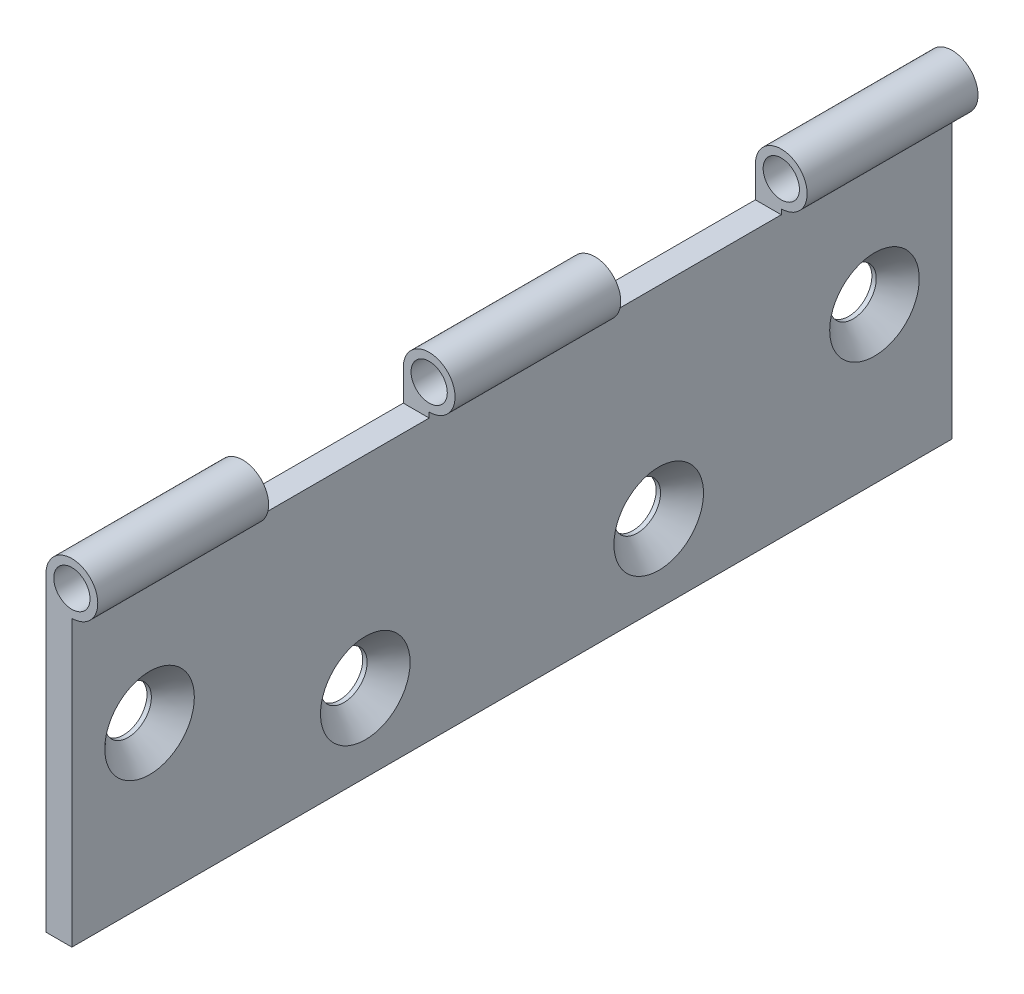
SolidWorks part; units mm, degrees
ref_plane "Front" through (0, 0, 0) normal (0, 0, 1) x (1, 0, 0)
ref_plane "Top" through (0, 0, 0) normal (0, 1, 0) x (1, 0, 0)
ref_plane "Right" through (0, 0, 0) normal (1, 0, 0) x (0, 0, -1)
sketch "Sketch1" plane through (0, 0, 0) normal (0, 0, 1) x (1, 0, 0)
  line L0 (0, 0) -> (0, 60)
  dimension "D1" = 60
extrude "Extrude-Thin1" add sketch "Sketch1" along normal mid plane 170 thin
sketch "Sketch3" plane through (0, 0, 85) normal (0, 0, 1) x (1, 0, 0)
  line L1 (0, 0) -> (0, 60) construction
  circle A0 centre (5, 60) radius 5
sweep "Sweep1" add profiles "Sketch3" path edge at (5, 60, 0)
sketch "Sketch4" plane through (0, 0, 85) normal (0, 0, 1) x (1, 0, 0)
  circle A0 centre (5, 60) radius 3.5
  dimension "D1" = 7
extrude "Cut-Extrude1" cut sketch "Sketch4" against normal through all
hole_wizard "CSK for M8 Flat Head Machine Screw1" positions "Sketch6" profile "Sketch5" countersink size "M8" standard "ANSI Metric" end condition through all
sketch "Sketch6" plane through (5, 0, 0) normal (1, 0, 0) x (0, 0, -1)
  line L0 (-85, 0) -> (-85, 55) construction
  line L1 (-85, 0) -> (85, 0) construction
  point P0 (-70, 30)
  point P2 (-28.3333, 15)
  dimension "D1" = 15
  dimension "D2" = 30
  dimension "D3" = 15
  dimension "D4" = 56.6667
sketch "Sketch5" plane through (5, 30, 70) normal (0, 1, 0) x (0, 0, -1)
  line L0 (0, 0) -> (0, 5)
  line L1 (0, 5) -> (4.5, 5)
  line L2 (4.5, 5) -> (4.5, 4.15)
  line L3 (4.5, 4.15) -> (8.65, 0)
  line L5 (8.65, 0) -> (0, 0)
  line L6 (-4.5, 4.15) -> (-8.65, 0) construction
  line L11 (0, -6.35) -> (0, 107.95) construction
  dimension "Thru Hole Dia." = 9
  dimension "Thru Hole Depth" = 5
  dimension "Near C'Sink Dia." = 17.3
  dimension "Near C'Sink Angle" = 90
mirror "Mirror1" about plane through (0, 0, 0) normal (0, 0, 1) of "CSK for M8 Flat Head Machine Screw1"
sketch "layout for cuts" plane through (5, 0, 0) normal (1, 0, 0) x (0, 0, -1)
  line L1 (-85, 65) -> (-85, 55) construction
  line L2 (85, 54) -> (-85, 54)
  line L3 (85, 54) -> (-85, 54)
  line L4 (85, 55) -> (85, 65) construction
  line L5 (-85, 65) -> (-85, 54)
  line L6 (85, 54) -> (85, 65)
  line L7 (-85, 65) -> (85, 65)
  line L8 (-51, 54) -> (-51, 65)
  line L9 (-17, 65) -> (-17, 54)
  line L10 (0, 0) -> (0, 83.3989) construction
  line L11 (-85, 0) -> (85, 0) construction
  line L12 (17, 65) -> (17, 54)
  line L13 (51, 54) -> (51, 65)
  dimension "D2" = 34
  dimension "D3" = 34
  dimension "D1" = 1
sketch "Sketch9" plane through (5, 0, 0) normal (1, 0, 0) x (0, 0, -1)
  line L0 (85, 54) -> (-85, 54) construction
  line L2 (-85, 65) -> (85, 65) construction
  line L4 (52, 54) -> (16, 54)
  line L5 (-16, 54) -> (-52, 54)
  line L6 (-52, 65) -> (-16, 65)
  line L10 (-52, 54) -> (-52, 65)
  line L11 (-52, 54) -> (-52, 65)
  line L13 (-16, 65) -> (-16, 54)
  line L14 (-16, 65) -> (-16, 54)
  line L16 (16, 65) -> (16, 54)
  line L17 (16, 65) -> (16, 54)
  line L18 (16, 65) -> (52, 65)
  line L19 (52, 54) -> (52, 65)
  line L20 (52, 54) -> (52, 65)
  dimension "D1" = 1
  dimension "D2" = 1
  dimension "D3" = 1
  dimension "D4" = 1
extrude "2Cuts" cut sketch "Sketch9" against normal through all and the other way through all
sketch "Sketch8" plane through (5, 0, 0) normal (1, 0, 0) x (0, 0, -1)
  line L0 (85, 54) -> (-85, 54) construction
  line L1 (-85, 65) -> (-85, 54) construction
  line L2 (-85, 65) -> (85, 65) construction
  line L3 (85, 54) -> (85, 65) construction
  line L4 (85, 54) -> (50, 54)
  line L5 (-85, 65) -> (-85, 54)
  line L6 (-85, 65) -> (-50, 65)
  line L7 (85, 54) -> (85, 65)
  line L10 (-50, 54) -> (-50, 65)
  line L11 (-50, 54) -> (-50, 65)
  line L13 (50, 54) -> (50, 65)
  line L14 (50, 54) -> (50, 65)
  line L16 (18, 65) -> (18, 54)
  line L17 (18, 65) -> (18, 54)
  line L18 (-18, 65) -> (18, 65)
  line L19 (-18, 65) -> (-18, 54)
  line L20 (-18, 65) -> (-18, 54)
  line L21 (-50, 54) -> (-85, 54)
  line L22 (50, 65) -> (85, 65)
  line L23 (18, 54) -> (-18, 54)
  dimension "D1" = 1
  dimension "D2" = 1
  dimension "D3" = 1
  dimension "D4" = 1
extrude "3Cuts" [suppressed] cut sketch "Sketch8" against normal through all and the other way through all
equation "\"D2@Sketch6\"= \"D1@Sketch1\" / 2"
equation "\"D4@Sketch6\" = \"D1@Extrude-Thin1\" / 3"
equation "\"D2@layout for cuts\"= \"D1@Extrude-Thin1\" / 5"
equation "\"D3@layout for cuts\" = \"D1@Extrude-Thin1\" / 5"
